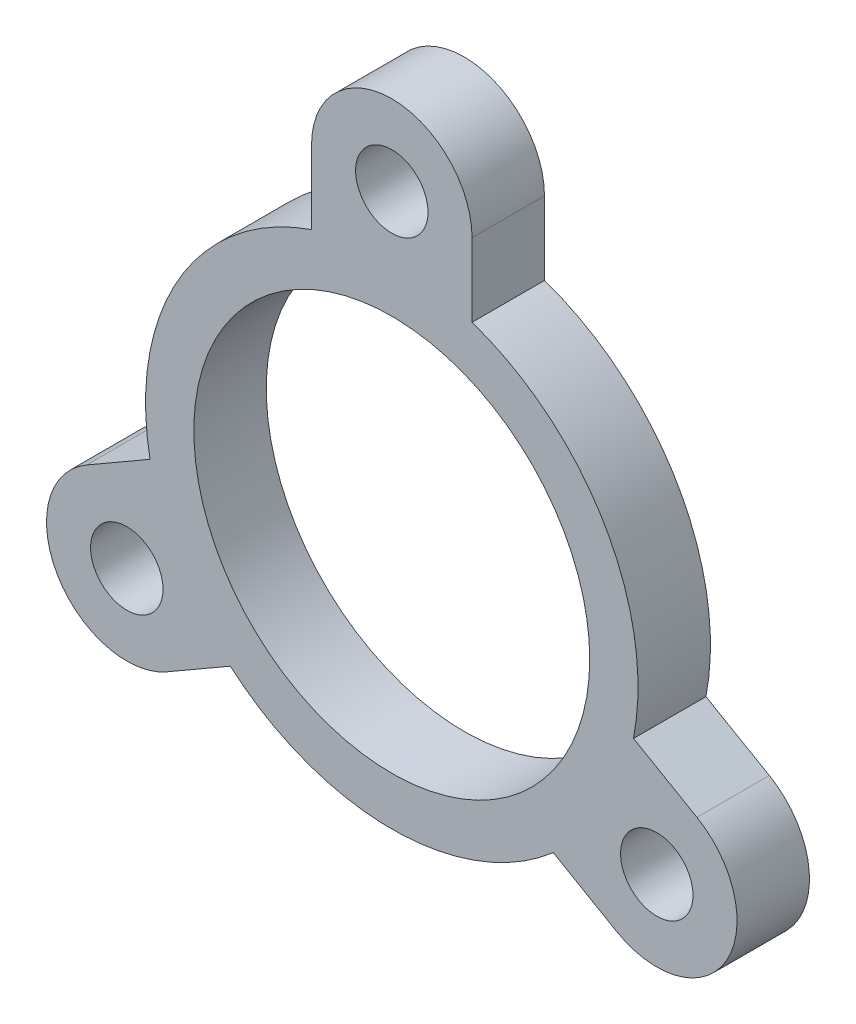
SolidWorks part; units mm, degrees
material "PETG"
ref_plane "Front Plane" through (0, 0, 0) normal (0, 0, 1) x (1, 0, 0)
ref_plane "Top Plane" through (0, 0, 0) normal (0, 1, 0) x (1, 0, 0)
ref_plane "Right Plane" through (0, 0, 0) normal (1, 0, 0) x (0, 0, -1)
sketch "Эскиз1" plane through (0, 0, 0) normal (0, 0, 1) x (1, 0, 0)
  line L0 (0, 12.675) -> (0, 0) construction
  line L1 (3.325, 12.675) -> (3.325, 0)
  line L2 (-3.325, 12.675) -> (-3.325, 0)
  line L3 (10.9769, -6.3375) -> (0, 0) construction
  line L4 (9.3144, -9.217) -> (-1.6625, -2.8795)
  line L5 (12.6394, -3.458) -> (1.6625, 2.8795)
  line L6 (-10.9769, -6.3375) -> (0, 0) construction
  line L7 (-12.6394, -3.458) -> (-1.6625, 2.8795)
  line L8 (-9.3144, -9.217) -> (1.6625, -2.8795)
  circle A0 centre (0, 0) radius 12.675 construction
  circle A1 centre (0, 0) radius 8.2
  circle A3 centre (0, 0) radius 16 construction
  circle A4 centre (0, 12.675) radius 1.5
  circle A5 centre (10.9769, -6.3375) radius 1.5
  circle A6 centre (-10.9769, -6.3375) radius 1.5
  arc A7 (3.325, 12.675) -> (-3.325, 12.675) centre (0, 12.675) ccw
  arc A8 (-3.325, 0) -> (3.325, 0) centre (0, 0) ccw
  arc A9 (9.3144, -9.217) -> (12.6394, -3.458) centre (10.9769, -6.3375) ccw
  arc A10 (1.6625, 2.8795) -> (-1.6625, -2.8795) centre (0, 0) ccw
  arc A11 (-12.6394, -3.458) -> (-9.3144, -9.217) centre (-10.9769, -6.3375) ccw
  arc A12 (1.6625, -2.8795) -> (-1.6625, 2.8795) centre (0, 0) ccw
  circle A13 centre (0, 0) radius 10.2
  point P8 (0, 6.3375)
  point P19 (5.4884, -3.1688)
  point P25 (-5.4884, -3.1687)
  dimension "D1" = 25.35
  dimension "D2" = 16.4
  dimension "D3" = 32
  dimension "D4" = 3
  dimension "D6" = 3
  dimension "D7" = 2
  dimension "D5" = 3
extrude "Бобышка-Вытянуть1" add sketch "Эскиз1" along normal mid plane 3 contours L2 A13 L7 A1 | L7 A13 L8 A1 | A13 L7 A11 L8 A6 | L8 A13 L4 A1 | L4 A13 L5 A1 | A13 L4 A9 L5 A5 | L5 A13 L1 A1 | L1 A13 L2 A1 | A13 L1 A7 L2 A4
